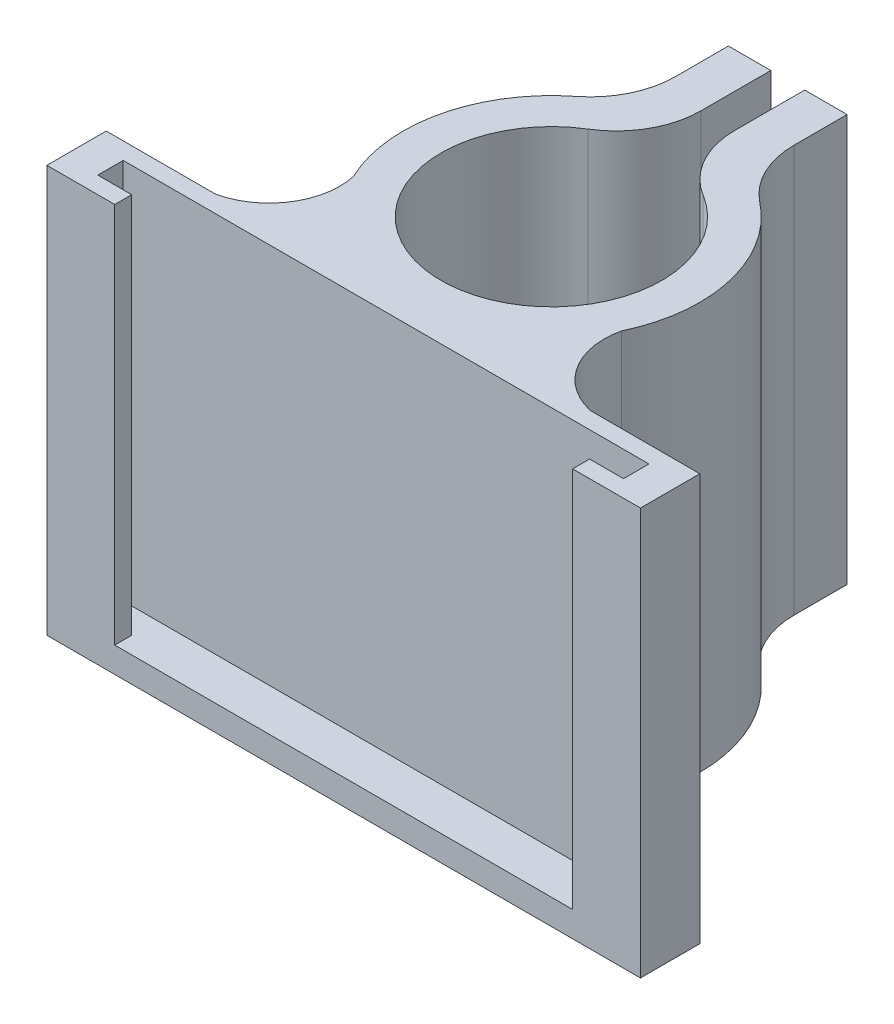
SolidWorks part; units mm, degrees
material "ABS"
ref_plane "Front Plane" through (0, 0, 0) normal (0, 0, 1) x (1, 0, 0)
ref_plane "Top Plane" through (0, 0, 0) normal (0, 1, 0) x (1, 0, 0)
ref_plane "Right Plane" through (0, 0, 0) normal (1, 0, 0) x (0, 0, -1)
sketch "Sketch1" plane through (0, 0, 0) normal (0, 1, 0) x (1, 0, 0)
  line L0 (0, -29.4402) -> (0, 28.6728) construction
  line L1 (-7, 16.039) -> (-7, 27.8705)
  line L2 (-7, 27.8705) -> (-2, 27.8705)
  line L3 (-2, 27.8705) -> (-2, 18.8705)
  line L4 (-2, 18.8705) -> (-2, 12.8705)
  line L5 (7, 27.8705) -> (2, 27.8705)
  line L6 (7, 16.039) -> (7, 27.8705)
  line L7 (2, 18.8705) -> (2, 12.8705)
  line L8 (2, 27.8705) -> (2, 18.8705)
  line L9 (22.0972, -17.5) -> (35, -17.5)
  line L10 (35, -17.5) -> (35, -24.5)
  line L11 (35, -24.5) -> (27, -24.5)
  line L12 (27, -24.5) -> (27, -22.5)
  line L13 (27, -22.5) -> (31, -22.5)
  line L14 (31, -22.5) -> (31, -19.5)
  line L15 (31, -19.5) -> (-31, -19.5)
  line L16 (-31, -22.5) -> (-31, -19.5)
  line L17 (-22.0972, -17.5) -> (-35, -17.5)
  line L18 (-27, -24.5) -> (-27, -22.5)
  line L19 (-35, -24.5) -> (-27, -24.5)
  line L20 (-27, -22.5) -> (-31, -22.5)
  line L21 (-35, -17.5) -> (-35, -24.5)
  arc A1 (-2, 12.8705) -> (2, 12.8705) centre (0, 0) ccw
  arc A2 (-7, 16.039) -> (-15.7949, -7.5347) centre (0, 0) ccw
  arc A3 (22.0972, -17.5) -> (15.7949, -7.5347) centre (23.9287, -9.3662) cw
  arc A4 (15.7949, -7.5347) -> (7, 16.039) centre (0, 0) ccw
  arc A5 (-22.0972, -17.5) -> (-15.7949, -7.5347) centre (-23.9287, -9.3662) ccw
  point P25 (0, 0)
  point P30 (0, -19.5)
  dimension "D1" = 3
  dimension "D2" = 26.05
  dimension "D3" = 35
  dimension "D4" = 5
  dimension "D5" = 2
  dimension "D6" = 9
  dimension "D7" = 15
  dimension "D8" = 31
  dimension "D9" = 4
  dimension "D10" = 7
  dimension "D11" = 2
  dimension "D12" = 4
extrude "Boss-Extrude1" add sketch "Sketch1" along normal blind 45
fillet "Fillet1" radius 10 2 edges at (2, 22.5, -12.8705) (-2, 22.5, -12.8705)
sketch "Sketch3" plane through (0, 0, 0) normal (0, -1, 0) x (1, 0, 0)
  line L0 (7, -16.039) -> (7, -27.8705) construction
  line L1 (-35, 24.5) -> (35, 24.5)
  line L2 (-35, 24.5) -> (-35, 17.5)
  line L3 (-35, 17.5) -> (-22.0972, 17.5)
  line L4 (35, 24.5) -> (35, 17.5)
  line L5 (7, -27.8705) -> (2, -27.8705) construction
  line L6 (2, -27.8705) -> (2, -19.6507) construction
  line L7 (-2, -19.6507) -> (-2, -27.8705) construction
  line L8 (-2, -27.8705) -> (-7, -27.8705) construction
  line L9 (-7, -27.8705) -> (-7, -16.039) construction
  line L10 (7, -16.039) -> (7, -27.8705)
  line L11 (7, -27.8705) -> (2, -27.8705)
  line L12 (2, -27.8705) -> (2, -19.6507)
  line L13 (-2, -19.6507) -> (-2, -27.8705)
  line L14 (-2, -27.8705) -> (-7, -27.8705)
  line L15 (-7, -27.8705) -> (-7, -16.039)
  line L16 (22.0972, 17.5) -> (35, 17.5)
  arc A0 (22.0972, 17.5) -> (15.7949, 7.5347) centre (23.9287, 9.3662) ccw construction
  arc A1 (7, -16.039) -> (15.7949, 7.5347) centre (0, 0) ccw construction
  arc A2 (6.7883, -11.1162) -> (2, -19.6507) centre (12, -19.6507) ccw construction
  arc A3 (-2, -19.6507) -> (-6.7883, -11.1162) centre (-12, -19.6507) ccw construction
  arc A4 (-15.7949, 7.5347) -> (-7, -16.039) centre (0, 0) ccw construction
  arc A5 (6.7883, -11.1162) -> (-6.7883, -11.1162) centre (0, 0) ccw construction
  arc A6 (-15.7949, 7.5347) -> (-22.0972, 17.5) centre (-23.9287, 9.3662) ccw construction
  arc A7 (22.0972, 17.5) -> (15.7949, 7.5347) centre (23.9287, 9.3662) ccw
  arc A8 (7, -16.039) -> (15.7949, 7.5347) centre (0, 0) ccw
  arc A9 (6.7883, -11.1162) -> (2, -19.6507) centre (12, -19.6507) ccw
  arc A10 (-2, -19.6507) -> (-6.7883, -11.1162) centre (-12, -19.6507) ccw
  arc A11 (-15.7949, 7.5347) -> (-7, -16.039) centre (0, 0) ccw
  arc A12 (6.7883, -11.1162) -> (-6.7883, -11.1162) centre (0, 0) ccw
  arc A13 (-15.7949, 7.5347) -> (-22.0972, 17.5) centre (-23.9287, 9.3662) ccw
extrude "Boss-Extrude4" add sketch "Sketch3" along normal blind 3
fillet "Fillet2" radius 10 2 edges at (-7, 21, -16.039) (7, 21, -16.039)
